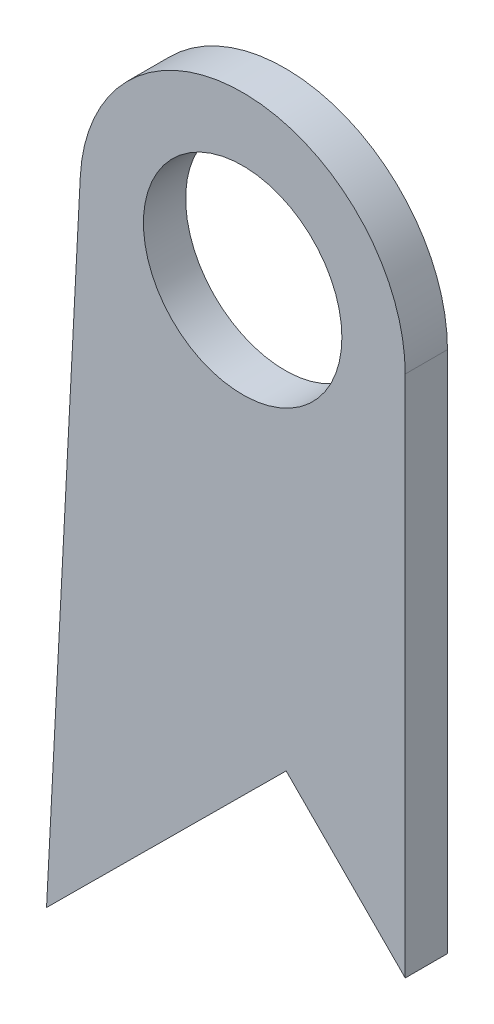
SolidWorks part; units mm, degrees
ref_plane "Plan de face" through (0, 0, 0) normal (0, 0, 1) x (1, 0, 0)
ref_plane "Plan de dessus" through (0, 0, 0) normal (0, 1, 0) x (1, 0, 0)
ref_plane "Plan de droite" through (0, 0, 0) normal (1, 0, 0) x (0, 0, -1)
sketch "Esquisse1" plane through (0, 0, 0) normal (0, 0, 1) x (1, 0, 0)
  line L0 (38.5, 0) -> (38.5, -123.8659)
  line L1 (38.5, -123.8659) -> (10.3052, -95.4924)
  line L2 (10.3052, -95.4924) -> (-46.4417, -151.8821)
  line L3 (-46.4417, -151.8821) -> (-38.4482, 1.9973)
  line L4 (10.3052, -95.4924) -> (52.8653, -53.2002) construction
  line L6 (38.5, -123.8659) -> (10.3052, -95.4924) construction
  line L7 (10.3052, -95.4924) -> (-40.8388, -44.0245) construction
  line L8 (0, 0) -> (10.3052, -95.4924) construction
  line L9 (0, 0) -> (81.0601, -81.5736) construction
  line L10 (81.0601, -81.5736) -> (38.5, -123.8659) construction
  circle A0 centre (0, 0) radius 23.5
  circle A1 centre (0, 0) radius 38.5 construction
  arc A2 (-38.4482, 1.9973) -> (38.5, 0) centre (0, 0) cw
  point P18 (0, 0)
  dimension "D1" = 47
  dimension "D2" = 90
  dimension "D3" = 60
  dimension "D4" = 40
  dimension "D6" = 80
  dimension "D7" = 115
  dimension "15" = 15
extrude "Boss.-Extru.1" add sketch "Esquisse1" along normal blind 10
